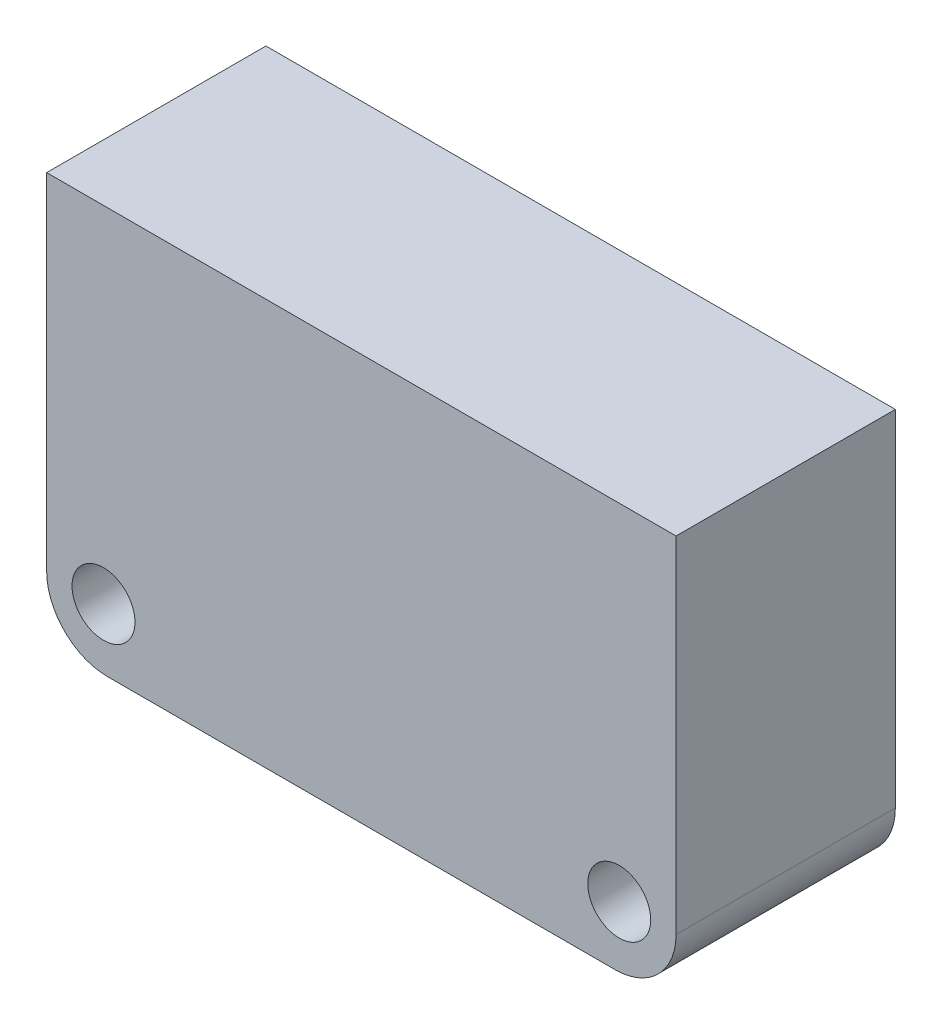
SolidWorks part; units mm, degrees
ref_plane "前视基准面" through (0, 0, 0) normal (0, 0, 1) x (1, 0, 0)
ref_plane "上视基准面" through (0, 0, 0) normal (0, 1, 0) x (1, 0, 0)
ref_plane "右视基准面" through (0, 0, 0) normal (1, 0, 0) x (0, 0, -1)
other "Configuration Table"
sketch "草图1" plane through (0, 0, 0) normal (0, 0, 1) x (1, 0, 0)
  line L1 (-15.5, 10) -> (15.5, 10)
  line L2 (-15.5, 10) -> (-15.5, -10)
  line L3 (-15.5, -10) -> (15.5, -10)
  line L4 (15.5, 10) -> (15.5, -10)
  line L5 (0, -10) -> (0, 10) construction
  line L6 (-15.5, 0) -> (15.5, 0) construction
  point P0 (0, 0)
  dimension "D1" = 31
  dimension "D2" = 20
extrude "凸台-拉伸1" add sketch "草图1" along normal blind 10.8
sketch "草图2" plane through (0, 0, 0) normal (0, 0, -1) x (-1, 0, 0)
  line L0 (-15.5, -10) -> (-15.5, 10) construction
  line L1 (15.5, -10) -> (-15.5, -10) construction
  circle A0 centre (-12.7, -7) radius 1.55
  circle A1 centre (12.7, -7) radius 1.55
  dimension "D3" = 3.1
  dimension "D4" = 3.1
  dimension "D1" = 25.4
  dimension "D2" = 2.8
  dimension "D5" = 3
  dimension "D6" = 3
extrude "切除-拉伸1" cut sketch "草图2" against normal through all
fillet "圆角1" radius 3 1 edges at (-15.5, -10, 5.4)
fillet "圆角2" radius 3 1 edges at (15.5, -10, 5.4)
sketch "草图3" plane through (0, -10, 0) normal (0, -1, 0) x (1, 0, 0)
  line L0 (-12.5, 10.8) -> (-12.5, 0) construction
  line L1 (-7.5, 7.9) -> (7.5, 7.9)
  line L2 (-7.5, 7.9) -> (-7.5, 2.9)
  line L3 (-7.5, 2.9) -> (7.5, 2.9)
  line L4 (7.5, 7.9) -> (7.5, 2.9)
  line L5 (0, 2.9) -> (0, 7.9) construction
  line L6 (-7.5, 5.4) -> (7.5, 5.4) construction
  line L7 (12.5, 0) -> (12.5, 10.8) construction
  point P0 (0, 5.4)
  dimension "D1" = 5.4
  dimension "D2" = 5
  dimension "D3" = 5
  dimension "D4" = 5
extrude "切除-拉伸2" cut sketch "草图3" against normal blind 3
